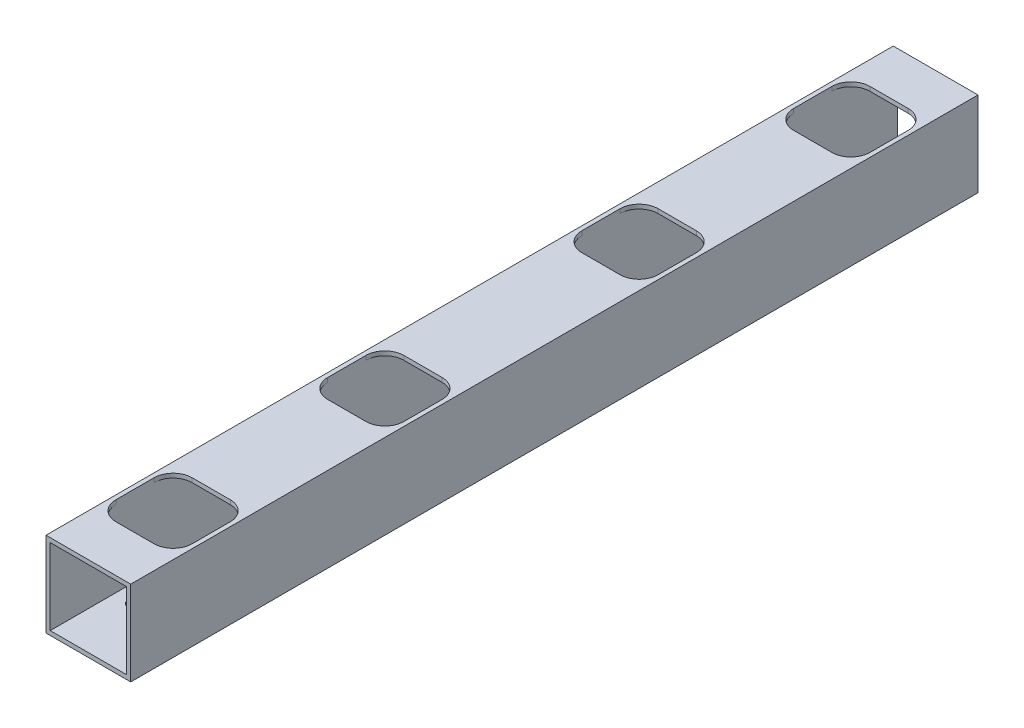
SolidWorks part; units mm, degrees
material "6061-T6 (SS)"
ref_plane "前视基准面" through (0, 0, 0) normal (0, 0, 1) x (1, 0, 0)
ref_plane "上视基准面" through (0, 0, 0) normal (0, 1, 0) x (1, 0, 0)
ref_plane "右视基准面" through (0, 0, 0) normal (1, 0, 0) x (0, 0, -1)
sketch "草图1" plane through (0, 0, 0) normal (0, 0, 1) x (1, 0, 0)
  line L1 (-10, 10) -> (10, 10)
  line L2 (-10, 10) -> (-10, -10)
  line L3 (-10, -10) -> (10, -10)
  line L4 (10, 10) -> (10, -10)
  line L5 (-10, 10) -> (10, -10) construction
  line L6 (-10, -10) -> (10, 10) construction
  line L7 (-9, 9) -> (9, 9)
  line L8 (-9, 9) -> (-9, -9)
  line L9 (-9, -9) -> (9, -9)
  line L10 (9, 9) -> (9, -9)
  line L11 (-9, 9) -> (9, -9) construction
  line L12 (-9, -9) -> (9, 9) construction
  point P0 (0, 0)
  point P6 (0, 0)
  dimension "D1" = 20
  dimension "D2" = 20
  dimension "D3" = 18
  dimension "D4" = 18
extrude "凸台-拉伸1" add sketch "草图1" along normal blind 200
sketch "草图3" plane through (0, 10, 0) normal (0, 1, 0) x (1, 0, 0)
  line L0 (-10, -140) -> (10, -120) construction
  line L5 (-10, -190) -> (10, -170) construction
  line L6 (-10, -170) -> (10, -170) construction
  line L7 (-10, -120) -> (10, -120) construction
  line L8 (-10, -120) -> (-10, -80) construction
  line L9 (-10, -80) -> (10, -80) construction
  line L10 (10, -120) -> (10, -80) construction
  line L11 (-10, -120) -> (10, -80) construction
  line L12 (-10, -80) -> (10, -120) construction
  line L13 (-10, -140) -> (10, -140) construction
  line L14 (-10, -140) -> (-10, -60) construction
  line L15 (-10, -60) -> (10, -60) construction
  line L16 (10, -140) -> (10, -60) construction
  line L17 (-10, -140) -> (10, -60) construction
  line L18 (-10, -60) -> (10, -140) construction
  line L19 (-10, -120) -> (10, -140) construction
  line L20 (4.5, -134.5) -> (13.5, -134.5) construction
  line L21 (-4.5, -134.5) -> (4.5, -134.5) construction
  line L22 (-4.5, -134.5) -> (-4.5, -125.5) construction
  line L23 (-4.5, -125.5) -> (4.5, -125.5) construction
  line L24 (4.5, -134.5) -> (4.5, -125.5) construction
  line L25 (-4.5, -134.5) -> (4.5, -125.5) construction
  line L26 (-4.5, -125.5) -> (4.5, -134.5) construction
  line L27 (4.5, -134.5) -> (4.5, -125.5) construction
  line L28 (4.5, -125.5) -> (13.5, -125.5) construction
  line L29 (4.5, -125.5) -> (4.5, -116.5) construction
  line L30 (-4.5, -125.5) -> (4.5, -125.5) construction
  line L31 (-4.5, -125.5) -> (-4.5, -116.5) construction
  line L32 (0, -100) -> (-32.7299, -100) construction
  line L33 (-10, -190) -> (10, -190) construction
  line L34 (-10, -170) -> (10, -190) construction
  line L35 (4.5, -184.5) -> (13.5, -184.5) construction
  line L36 (-4.5, -184.5) -> (4.5, -184.5) construction
  line L37 (-4.5, -184.5) -> (-4.5, -175.5) construction
  line L38 (-4.5, -175.5) -> (4.5, -175.5) construction
  line L39 (4.5, -184.5) -> (4.5, -175.5) construction
  line L40 (-4.5, -184.5) -> (4.5, -175.5) construction
  line L41 (-4.5, -175.5) -> (4.5, -184.5) construction
  line L42 (4.5, -184.5) -> (4.5, -175.5) construction
  line L43 (4.5, -175.5) -> (13.5, -175.5) construction
  line L44 (4.5, -175.5) -> (4.5, -166.5) construction
  line L45 (-4.5, -175.5) -> (4.5, -175.5) construction
  line L46 (-4.5, -175.5) -> (-4.5, -166.5) construction
  line L47 (-4.5, -24.5) -> (-4.5, -33.5) construction
  line L48 (-4.5, -24.5) -> (4.5, -24.5) construction
  line L49 (4.5, -24.5) -> (4.5, -33.5) construction
  line L50 (4.5, -24.5) -> (13.5, -24.5) construction
  line L51 (4.5, -15.5) -> (4.5, -24.5) construction
  line L52 (-4.5, -24.5) -> (4.5, -15.5) construction
  line L53 (-4.5, -15.5) -> (4.5, -24.5) construction
  line L54 (4.5, -15.5) -> (4.5, -24.5) construction
  line L55 (-4.5, -24.5) -> (4.5, -24.5) construction
  line L56 (-4.5, -15.5) -> (-4.5, -24.5) construction
  line L57 (-4.5, -15.5) -> (4.5, -15.5) construction
  line L58 (4.5, -15.5) -> (13.5, -15.5) construction
  line L59 (-10, -30) -> (10, -10) construction
  line L60 (-10, -10) -> (10, -10) construction
  line L61 (-10, -30) -> (10, -30) construction
  line L62 (-10, -10) -> (10, -30) construction
  circle A0 centre (-4.5, -134.5) radius 1.6
  circle A1 centre (4.5, -134.5) radius 1.6
  circle A2 centre (4.5, -125.5) radius 1.6
  circle A3 centre (-4.5, -125.5) radius 1.6
  circle A4 centre (4.5, -65.5) radius 1.6
  circle A5 centre (4.5, -74.5) radius 1.6
  circle A6 centre (-4.5, -74.5) radius 1.6
  circle A7 centre (-4.5, -65.5) radius 1.6
  circle A16 centre (-4.5, -184.5) radius 1.6
  circle A17 centre (4.5, -184.5) radius 1.6
  circle A18 centre (4.5, -175.5) radius 1.6
  circle A19 centre (-4.5, -175.5) radius 1.6
  circle A20 centre (-4.5, -24.5) radius 1.6
  circle A21 centre (4.5, -24.5) radius 1.6
  circle A22 centre (4.5, -15.5) radius 1.6
  circle A23 centre (-4.5, -15.5) radius 1.6
  point P4 (0, -100)
  point P7 (0, -100)
  point P12 (0, -100)
  point P17 (0, -130)
  point P46 (0, -180)
  point P79 (0, -20)
  dimension "D5" = 2
  dimension "D1" = 40
  dimension "D2" = 80
  dimension "D3" = 9
  dimension "D4" = 9
  dimension "D6" = 2
  dimension "D7" = 2
extrude "切除-拉伸1" cut sketch "草图3" against normal through all
sketch "草图4" plane through (0, 10, 0) normal (0, 1, 0) x (1, 0, 0)
  line L1 (-4.5, -65.5) -> (4.5, -65.5) construction
  line L2 (-4.5, -65.5) -> (-4.5, -74.5) construction
  line L3 (-4.5, -74.5) -> (4.5, -74.5) construction
  line L4 (4.5, -65.5) -> (4.5, -74.5) construction
  line L5 (-4.5, -65.5) -> (4.5, -74.5) construction
  line L6 (-4.5, -74.5) -> (4.5, -65.5) construction
  line L11 (-9, -61) -> (9, -79) construction
  line L12 (-9, -79) -> (9, -61) construction
  line L24 (-9, -11) -> (9, -11) construction
  line L25 (-9, -11) -> (-9, -29) construction
  line L26 (-9, -29) -> (9, -29) construction
  line L27 (9, -11) -> (9, -29) construction
  line L28 (-4.5, -15.5) -> (4.5, -15.5) construction
  line L29 (-4.5, -15.5) -> (-4.5, -24.5) construction
  line L30 (-4.5, -24.5) -> (4.5, -24.5) construction
  line L31 (4.5, -15.5) -> (4.5, -24.5) construction
  line L32 (-4.5, -15.5) -> (4.5, -24.5) construction
  line L33 (-4.5, -24.5) -> (4.5, -15.5) construction
  line L34 (-9, -11) -> (9, -29) construction
  line L35 (-9, -29) -> (9, -11) construction
  line L40 (4.5, -11) -> (-4.5, -11)
  line L41 (-9, -15.5) -> (-9, -24.5)
  line L42 (9, -15.5) -> (9, -24.5)
  line L43 (4.5, -29) -> (-4.5, -29)
  line L44 (4.5, -79) -> (-4.5, -79)
  line L45 (-9, -65.5) -> (-9, -74.5)
  line L46 (4.5, -61) -> (-4.5, -61)
  line L47 (9, -65.5) -> (9, -74.5)
  line L48 (9, -134.5) -> (9, -125.5)
  line L49 (10, 0) -> (-10, 0) construction
  line L50 (10, 0) -> (10, -200) construction
  line L51 (10, -200) -> (-10, -200) construction
  line L52 (-10, 0) -> (-10, -200) construction
  line L53 (0, -200) -> (0, 0) construction
  line L54 (10, -100) -> (-10, -100) construction
  line L55 (4.5, -139) -> (-4.5, -139)
  line L56 (-9, -134.5) -> (-9, -125.5)
  line L57 (4.5, -121) -> (-4.5, -121)
  line L58 (9, -184.5) -> (9, -175.5)
  line L59 (4.5, -189) -> (-4.5, -189)
  line L60 (-9, -184.5) -> (-9, -175.5)
  line L61 (4.5, -171) -> (-4.5, -171)
  arc A0 (-4.5, -11) -> (-9, -15.5) centre (-4.5, -15.5) ccw
  arc A1 (9, -15.5) -> (4.5, -11) centre (4.5, -15.5) ccw
  arc A2 (4.5, -29) -> (9, -24.5) centre (4.5, -24.5) ccw
  arc A3 (-9, -24.5) -> (-4.5, -29) centre (-4.5, -24.5) ccw
  arc A4 (-9, -74.5) -> (-4.5, -79) centre (-4.5, -74.5) ccw
  arc A5 (-4.5, -61) -> (-9, -65.5) centre (-4.5, -65.5) ccw
  arc A6 (9, -65.5) -> (4.5, -61) centre (4.5, -65.5) ccw
  arc A7 (4.5, -79) -> (9, -74.5) centre (4.5, -74.5) ccw
  arc A8 (4.5, -121) -> (9, -125.5) centre (4.5, -125.5) cw
  arc A9 (9, -134.5) -> (4.5, -139) centre (4.5, -134.5) cw
  arc A10 (-4.5, -139) -> (-9, -134.5) centre (-4.5, -134.5) cw
  arc A11 (-9, -125.5) -> (-4.5, -121) centre (-4.5, -125.5) cw
  arc A12 (4.5, -171) -> (9, -175.5) centre (4.5, -175.5) cw
  arc A13 (9, -184.5) -> (4.5, -189) centre (4.5, -184.5) cw
  arc A14 (-4.5, -189) -> (-9, -184.5) centre (-4.5, -184.5) cw
  arc A15 (-9, -175.5) -> (-4.5, -171) centre (-4.5, -175.5) cw
  point P5 (0, -70)
  point P6 (0, -70)
  point P26 (0, -20)
  point P27 (0, -20)
  point P145 (0, -100)
  dimension "D1" = 18
  dimension "D2" = 18
  dimension "D5" = 2
  dimension "D7" = 2
  dimension "D6" = 4
extrude "切除-拉伸2" cut sketch "草图4" against normal up to next
